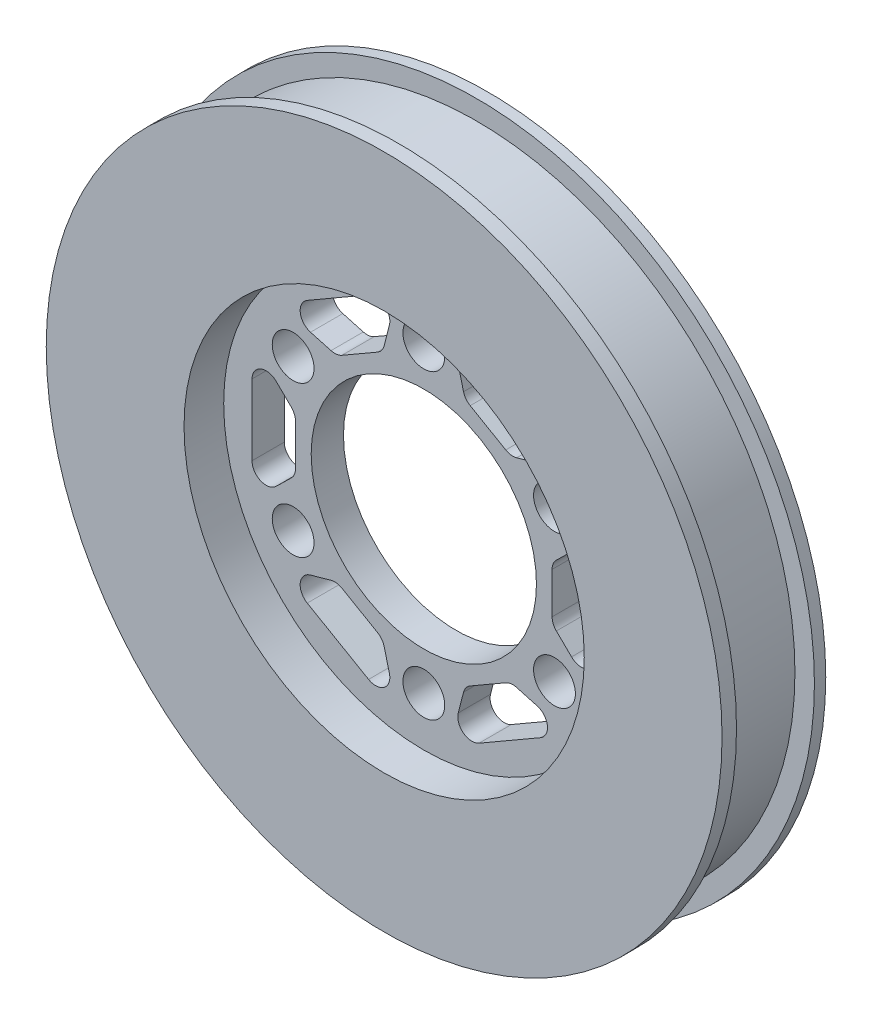
SolidWorks part; units mm, degrees
ref_plane "Piano frontale" through (0, 0, 0) normal (0, 0, 1) x (1, 0, 0)
ref_plane "Piano superiore" through (0, 0, 0) normal (0, 1, 0) x (1, 0, 0)
ref_plane "Piano destro" through (0, 0, 0) normal (1, 0, 0) x (0, 0, -1)
sketch "Schizzo1" plane through (0, 0, 0) normal (0, 0, 1) x (1, 0, 0)
  circle A0 centre (0, 0) radius 23.85
  dimension "D1" = 47.7
extrude "Estrusione-Estrusione1" add sketch "Schizzo1" along normal blind 0.8
sketch "Schizzo2" plane through (0, 0, 0.8) normal (0, 0, 1) x (1, 0, 0)
  circle A0 centre (0, 0) radius 22.475
  dimension "D1" = 44.95
extrude "Estrusione-Estrusione2" add sketch "Schizzo2" along normal blind 5.5
sketch "Schizzo3" plane through (0, 0, 6.3) normal (0, 0, 1) x (1, 0, 0)
  circle A0 centre (0, 0) radius 23.85 construction
  circle A1 centre (0, 0) radius 23.85
extrude "Estrusione-Estrusione3" add sketch "Schizzo3" along normal blind 1.02
sketch "Schizzo4" plane through (0, 0, 0) normal (0, 0, -1) x (-1, 0, 0)
  circle A0 centre (0, 0) radius 20.665
  dimension "D1" = 41.33
extrude "Taglio-Estrusione1" cut sketch "Schizzo4" against normal blind 1.27
sketch "Schizzo5" plane through (0, 0, 1.27) normal (0, 0, -1) x (-1, 0, 0)
  circle A0 centre (0, 0) radius 16.975
  dimension "D1" = 33.95
extrude "Taglio-Estrusione2" cut sketch "Schizzo5" against normal blind 0.97
sketch "Schizzo6" plane through (0, 0, 2.24) normal (0, 0, -1) x (-1, 0, 0)
  circle A0 centre (0, 0) radius 7.95
  dimension "D1" = 15.9
extrude "Taglio-Estrusione3" cut sketch "Schizzo6" against normal through all
sketch "Schizzo7" plane through (0, 0, 7.32) normal (0, 0, 1) x (1, 0, 0)
  circle A0 centre (0, 0) radius 14.125
  dimension "D1" = 28.25
extrude "Taglio-Estrusione4" cut sketch "Schizzo7" against normal blind 2.8
sketch "Schizzo10" plane through (0, 0, 2.24) normal (0, 0, -1) x (-1, 0, 0)
  line L0 (-12.1259, 2.5) -> (-12.1259, -2.5)
  line L1 (-9.0547, 1.45) -> (-9.0547, -1.45)
  line L2 (-10.4259, 3.2141) -> (-9.3547, 2.1641)
  line L3 (-9.3547, -2.1641) -> (-10.4259, -3.2141)
  line L4 (-12.1259, 0) -> (0, 0) construction
  line L5 (-2.4294, 10.6361) -> (-2.8031, 9.1834)
  line L6 (-3.2716, 8.5666) -> (-5.7831, 7.1166)
  line L7 (-3.8979, 11.7513) -> (-8.228, 9.2513)
  line L8 (-6.5515, 7.0193) -> (-7.9965, 7.422)
  line L9 (7.9965, 7.422) -> (6.5515, 7.0193)
  line L10 (5.7831, 7.1166) -> (3.2716, 8.5666)
  line L11 (8.228, 9.2513) -> (3.8979, 11.7513)
  line L12 (2.8031, 9.1834) -> (2.4294, 10.6361)
  line L13 (10.4259, -3.2141) -> (9.3547, -2.1641)
  line L14 (9.0547, -1.45) -> (9.0547, 1.45)
  line L15 (12.1259, -2.5) -> (12.1259, 2.5)
  line L16 (9.3547, 2.1641) -> (10.4259, 3.2141)
  line L17 (2.4294, -10.6361) -> (2.8031, -9.1834)
  line L18 (3.2716, -8.5666) -> (5.7831, -7.1166)
  line L19 (3.8979, -11.7513) -> (8.228, -9.2513)
  line L20 (6.5515, -7.0193) -> (7.9965, -7.422)
  line L21 (-7.9965, -7.422) -> (-6.5515, -7.0193)
  line L22 (-5.7831, -7.1166) -> (-3.2716, -8.5666)
  line L23 (-8.228, -9.2513) -> (-3.8979, -11.7513)
  line L24 (-2.8031, -9.1834) -> (-2.4294, -10.6361)
  circle A0 centre (0, 0) radius 10.65 construction
  circle A1 centre (0, 10.65) radius 1.475
  circle A2 centre (9.2232, 5.325) radius 1.475
  arc A3 (-3.8979, 11.7513) -> (-2.4294, 10.6361) centre (-3.3979, 10.8853) cw
  arc A4 (-8.228, 9.2513) -> (-7.9965, 7.422) centre (-7.728, 8.3853) ccw
  arc A5 (-5.7831, 7.1166) -> (-6.5515, 7.0193) centre (-6.2831, 7.9826) cw
  circle A6 centre (9.2232, -5.325) radius 1.475
  arc A7 (-9.0547, 1.45) -> (-9.3547, 2.1641) centre (-10.0547, 1.45) ccw
  arc A8 (-9.0547, -1.45) -> (-9.3547, -2.1641) centre (-10.0547, -1.45) cw
  arc A9 (-12.1259, -2.5) -> (-10.4259, -3.2141) centre (-11.1259, -2.5) ccw
  arc A10 (-12.1259, 2.5) -> (-10.4259, 3.2141) centre (-11.1259, 2.5) cw
  arc A11 (8.228, 9.2513) -> (7.9965, 7.422) centre (7.728, 8.3853) cw
  arc A12 (3.8979, 11.7513) -> (2.4294, 10.6361) centre (3.3979, 10.8853) ccw
  arc A13 (3.2716, 8.5666) -> (2.8031, 9.1834) centre (3.7716, 9.4326) cw
  circle A14 centre (0, -10.65) radius 1.475
  arc A15 (12.1259, -2.5) -> (10.4259, -3.2141) centre (11.1259, -2.5) cw
  arc A16 (12.1259, 2.5) -> (10.4259, 3.2141) centre (11.1259, 2.5) ccw
  arc A17 (9.0547, 1.45) -> (9.3547, 2.1641) centre (10.0547, 1.45) cw
  circle A18 centre (-9.2232, -5.325) radius 1.475
  arc A19 (3.8979, -11.7513) -> (2.4294, -10.6361) centre (3.3979, -10.8853) cw
  arc A20 (8.228, -9.2513) -> (7.9965, -7.422) centre (7.728, -8.3853) ccw
  arc A21 (5.7831, -7.1166) -> (6.5515, -7.0193) centre (6.2831, -7.9826) cw
  circle A22 centre (-9.2232, 5.325) radius 1.475
  arc A23 (-8.228, -9.2513) -> (-7.9965, -7.422) centre (-7.728, -8.3853) cw
  arc A24 (-3.8979, -11.7513) -> (-2.4294, -10.6361) centre (-3.3979, -10.8853) ccw
  arc A25 (-3.2716, -8.5666) -> (-2.8031, -9.1834) centre (-3.7716, -9.4326) cw
  arc A26 (-3.2716, 8.5666) -> (-2.8031, 9.1834) centre (-3.7716, 9.4326) ccw
  arc A27 (5.7831, 7.1166) -> (6.5515, 7.0193) centre (6.2831, 7.9826) ccw
  arc A28 (9.0547, -1.45) -> (9.3547, -2.1641) centre (10.0547, -1.45) ccw
  arc A29 (3.2716, -8.5666) -> (2.8031, -9.1834) centre (3.7716, -9.4326) ccw
  arc A30 (-5.7831, -7.1166) -> (-6.5515, -7.0193) centre (-6.2831, -7.9826) ccw
  point P5 (-12.1259, 0)
  point P86 (0, 0)
  point P103 (0, 0)
  dimension "D1" = 21.3
  dimension "D2" = 2.95
  dimension "D4" = 1
  dimension "D5" = 5
  dimension "D6" = 1.5
  dimension "D3" = 2.9
  dimension "D7" = 6
  dimension "D8" = 6
extrude "Taglio-Estrusione5" cut sketch "Schizzo10" against normal through all
